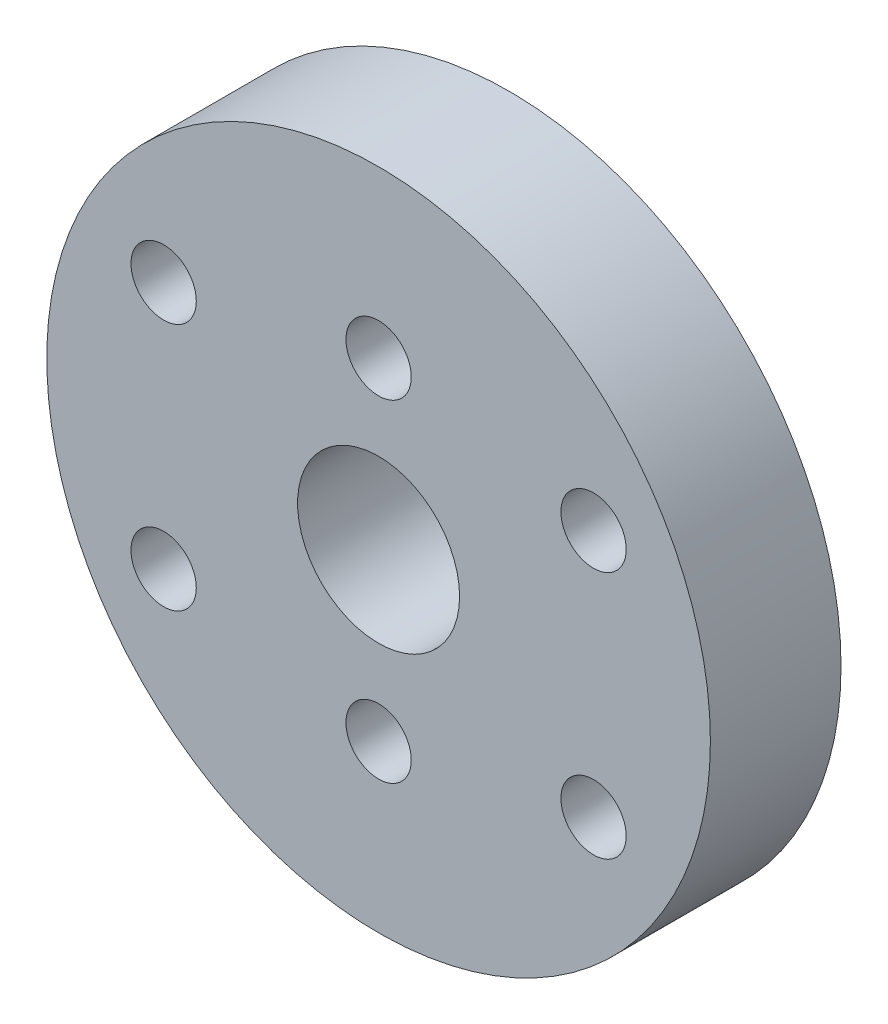
SolidWorks part; units mm, degrees
ref_plane "Plan de face" through (0, 0, 0) normal (0, 0, 1) x (1, 0, 0)
ref_plane "Plan de dessus" through (0, 0, 0) normal (0, 1, 0) x (1, 0, 0)
ref_plane "Plan de droite" through (0, 0, 0) normal (1, 0, 0) x (0, 0, -1)
sketch "Esquisse1" plane through (0, 0, 0) normal (0, 0, 1) x (1, 0, 0)
  circle A0 centre (0, 0) radius 12.7
  circle A1 centre (0, 0) radius 9.5 construction
  circle A2 centre (0, 6.35) radius 1.25
  circle A3 centre (0, 0) radius 6.35 construction
  circle A4 centre (8.2272, 4.75) radius 1.25
  circle A5 centre (8.2272, -4.75) radius 1.25
  circle A6 centre (0, -6.35) radius 1.25
  circle A7 centre (-8.2272, -4.75) radius 1.25
  circle A8 centre (0, 0) radius 3.1
  circle A10 centre (-8.2272, 4.75) radius 1.25
  point P19 (0, 0)
  point P25 (0, 0)
  point P26 (0, 0)
  dimension "D1" = 25.4
  dimension "D2" = 2
extrude "Boss.-Extru.1" add sketch "Esquisse1" along normal blind 5
